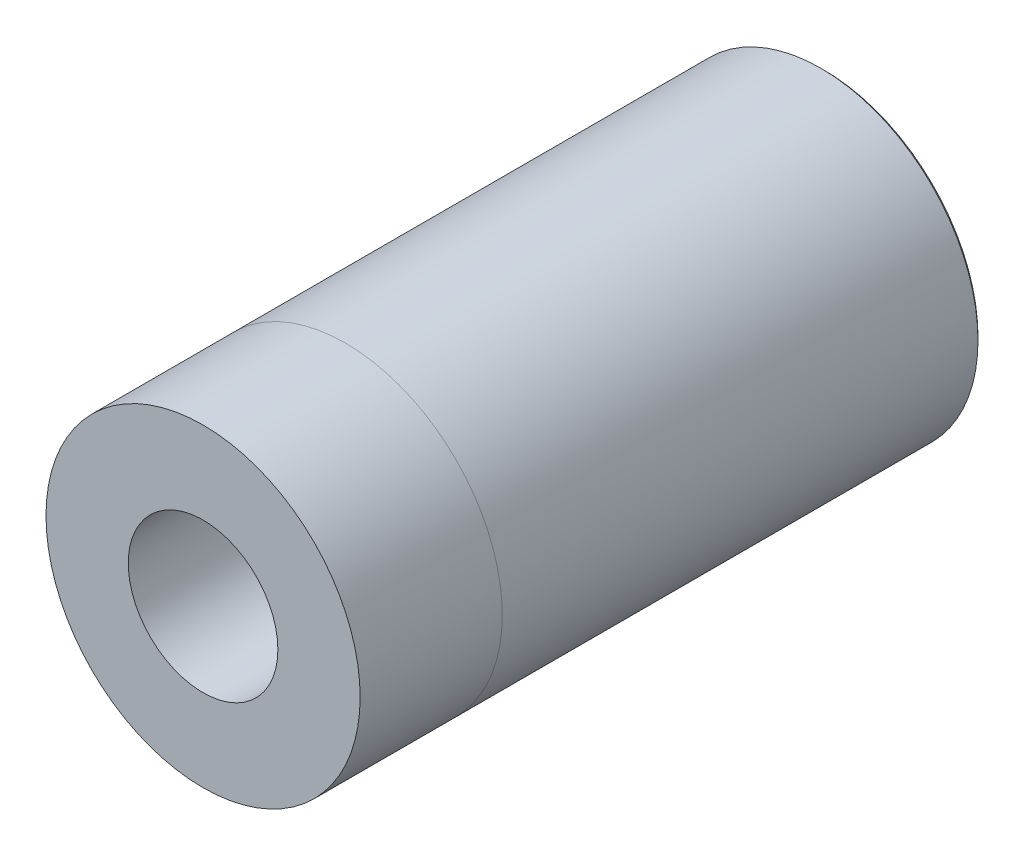
SolidWorks part; units mm, degrees
material "6061 合金"
ref_plane "前视基准面" through (0, 0, 0) normal (0, 0, 1) x (1, 0, 0)
ref_plane "上视基准面" through (0, 0, 0) normal (0, 1, 0) x (1, 0, 0)
ref_plane "右视基准面" through (0, 0, 0) normal (1, 0, 0) x (0, 0, -1)
sketch "草图1" plane through (0, 0, 0) normal (0, 0, 1) x (1, 0, 0)
  circle A0 centre (0, 0) radius 10.5
  dimension "D1" = 21
extrude "拉伸1" add sketch "草图1" along normal blind 32
sketch "草图2" plane through (0, 0, 32) normal (0, 0, 1) x (1, 0, 0)
  circle A0 centre (0, 0) radius 10.5
extrude "拉伸2" add sketch "草图2" along normal blind 9.5 separate body
sketch "草图3" plane through (0, 0, 41.5) normal (0, 0, 1) x (1, 0, 0)
  circle A0 centre (0, 0) radius 5
  dimension "D1" = 10
extrude "拉伸3" cut sketch "草图3" against normal through all
chamfer "倒角1" distance 0.2 angle 45 1 edges at (10.5, 0, 0)
